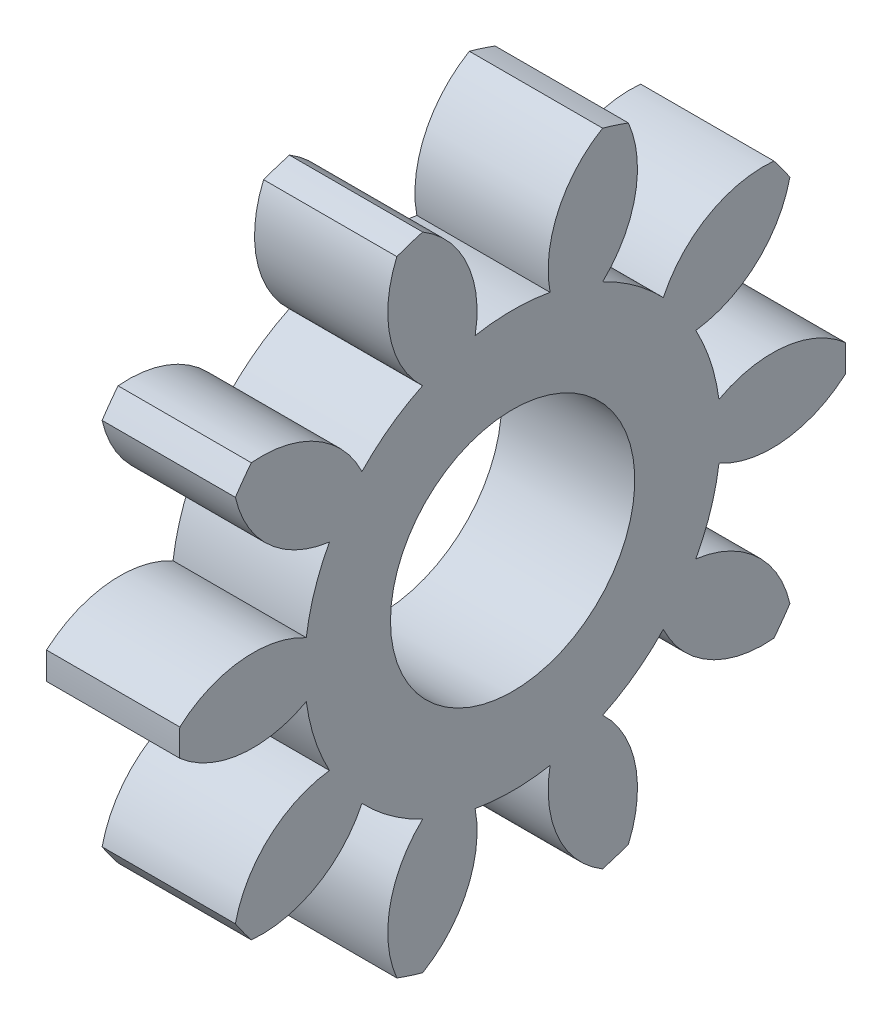
SolidWorks part; units mm, degrees
ref_plane "Plane1" through (0, 0, 0) normal (0, 0, 1) x (1, 0, 0)
ref_plane "Plane2" through (0, 0, 0) normal (0, 1, 0) x (1, 0, 0)
ref_plane "Plane3" through (0, 0, 0) normal (1, 0, 0) x (0, 0, -1)
sketch "HoldingSke" plane through (0, 0, 0) normal (0, 1, 0) x (1, 0, 0)
  line L0 (0, 0) -> (0.197, -0.0347)
  line L1 (-15, 0) -> (100, 0) construction
  line L2 (0, 0) -> (-2.1039, 2.3779)
  line L3 (0, 0) -> (-11.863, 4.5341)
  line L4 (0, 0) -> (8.5048, 1.4996)
  line L5 (0, 0) -> (-46.8476, -17.4728)
  line L6 (0, 0) -> (-9.9476, -6.7116)
  line L7 (-2.1039, 2.3779) -> (8.6586, 51.2059)
  line L8 (-76.2, 54.61) -> (-72.9, 54.61)
  line L9 (-67.7845, 28.3722) -> (-49.3413, 33.142)
  line L10 (-76.2, 71.12) -> (104.1128, 71.12)
  line L11 (0, 0) -> (-12, 0)
  line L12 (-76.2, 101.6) -> (-76.033, 101.6)
  line L13 (24.9733, 27.94) -> (52.9518, 28.4284)
  line L14 (24.9733, 27.94) -> (24.9743, 27.94)
  line L15 (24.9733, 27.94) -> (100.4006, 29.5858)
  line L16 (-63.627, -5) -> (-12.827, -5)
  circle A0 centre (0, 0) radius 11
  circle A1 centre (0, 0) radius 18.749
  circle A2 centre (0, 0) radius 37.5
  circle A3 centre (0, 0) radius 11
  dimension "MHD" = 37.498
  dimension "Hub_dia" = 75
  dimension "Bore" = 22
  dimension "MBD" = 22
  dimension "Num_teeth" = 10
  dimension "Pitch_radius" = 180.3128
  dimension "Pitch" = 0.2
  dimension "Width" = 12
  dimension "Overall_len" = 50
  dimension "Show_teeth" = 10
  dimension "Thickness" = 12
  dimension "OAL" = 50.0001
  dimension "T_dim" = 3.3
  dimension "Ap" = 14.5
  dimension "H" = 19.05
  dimension "Backlash" = 0.167
  dimension "Addendum_fac" = 1
  dimension "Dedendum_fac" = 1.25
  dimension "Clearance_fac" = 0.25
  dimension "Dedendum_add" = 0.001
  dimension "Module" = 5
sketch "BasProSke" plane through (0, 0, 0) normal (0, 1, 0) x (1, 0, 0)
  line L0 (-10, 0) -> (60, 0) construction
  line L1 (0, 0) -> (0, 30)
  line L2 (0, 0) -> (12, 0)
  line L3 (12, 0) -> (12, 30)
  line L4 (12, 30) -> (0, 30)
  dimension "Diameter" = 60
  dimension "Thickness" = 12
revolve "Base-Revolve" add sketch "BasProSke" angle 360 about L0
sketch "TooCutSke" plane through (0, 0, 0) normal (1, 0, 0) x (0, 0, -1)
  line L1 (0, 0) -> (0, 107) construction
  line L2 (0, 0) -> (-4.2026, 24.6442) construction
  line L3 (0, 0) -> (-15.2881, 47.0521) construction
  line L4 (-4.2026, 24.6442) -> (-7.6441, 23.526) construction
  arc A0 (3.374, 18.4429) -> (-3.374, 18.4429) centre (0, 0) ccw
  arc A1 (8.1303, 28.9037) -> (-8.1303, 28.9037) centre (0, 0) ccw
  circle A2 centre (0, 0) radius 25 construction
  circle A3 centre (0, 0) radius 24.2037 construction
  arc A4 (-3.374, 18.4429) -> (-8.1303, 28.9037) centre (-13.2027, 20.2856) ccw
  arc A5 (8.1303, 28.9037) -> (3.374, 18.4429) centre (13.2027, 20.2856) ccw
  dimension "Root_dia" = 37.498
  dimension "Overcut_dia" = 60.0508
  dimension "Pitch_dia" = 50
  dimension "Base_dia" = 48.4074
  dimension "Flank_rad" = 10
  dimension "Half_ang" = 18
  dimension "Half_CT" = 3.6186
extrude "ToothCut" cut sketch "TooCutSke" along normal through all
fillet "Breaks" [suppressed] radius 0.1
fillet "RootFillets" [suppressed] radius 1.251
pattern_circular "TeethCuts" count 10 every 36 about axis through (-10, 0, 0) along (1, 0, 0) of "ToothCut", "RootFillets", "Breaks"
sketch "HubNeaOneSke" plane through (0, 0, 0) normal (-1, 0, 0) x (0, 0, 1)
  circle A0 centre (0, 0) radius 18.749
  dimension "Diameter" = 37.498
extrude "HubNearOne" [suppressed] add sketch "HubNeaOneSke" along normal blind 38.0001
sketch "HubNeaBotSke" plane through (0, 0, 0) normal (-1, 0, 0) x (0, 0, 1)
  circle A0 centre (0, 0) radius 18.749
  dimension "Diameter" = 37.498
extrude "HubNearBoth" [suppressed] add sketch "HubNeaBotSke" along normal blind 19
ref_plane "FarPln" through (12, 0, 0) normal (1, 0, 0) x (0, 0, -1)
sketch "HubFarSke" plane through (12, 0, 0) normal (1, 0, 0) x (0, 0, -1)
  circle A0 centre (0, 0) radius 18.749
  dimension "Diameter" = 37.498
extrude "HubFar" [suppressed] add sketch "HubFarSke" along normal blind 19
sketch "BorSke" plane through (0, 0, 0) normal (1, 0, 0) x (0, 0, -1)
  circle A0 centre (0, 0) radius 11
  dimension "Diameter" = 22
extrude "Bore" cut sketch "BorSke" along normal mid plane 100.0001
sketch "KeySke" plane through (0, 0, 0) normal (1, 0, 0) x (0, 0, -1)
  line L0 (-4, 0) -> (-4, 14.3)
  line L1 (-4, 14.3) -> (4, 14.3)
  line L2 (4, 14.3) -> (4, 0)
  line L3 (0, 0) -> (0, 34) construction
  line L4 (-4, 0) -> (4, 0)
  dimension "Offset" = 14.3
  dimension "Width" = 8
extrude "Keyway" [suppressed] cut sketch "KeySke" along normal mid plane 100.0001
pattern_circular "Keyway2" [suppressed] count 2 every 90 about axis through (-10, 0, 0) along (1, 0, 0)
equation "' \"Module@HoldingSke\" = 6.35"
equation "' \"Num_teeth@HoldingSke\" = 12"
equation "' \"Ap@HoldingSke\" =  20"
equation "' \"Width@HoldingSke\" = 0.5 * 25.4"
equation "' \"Hub_dia@HoldingSke\"= 1 * 25.4"
equation "' \"Overall_len@HoldingSke\" = 1.0 * 25.4"
equation "' \"Bore@HoldingSke\" = 0.75 * 25.4"
equation "' \"T_dim@HoldingSke\" = 0.1 * 25.4"
equation "' \"Width@KeySke\" = 0.25 * 25.4"
equation "' \"Show_teeth@HoldingSke\" = 13"
equation "' \"Backlash@HoldingSke\" = 0.009 * 25.4"
equation "' \"Addendum_fac@HoldingSke\" = 1.0"
equation "' \"Dedendum_fac@HoldingSke\" = 1.25"
equation "' \"Dedendum_add@HoldingSke\" = 0.00005 * 25.4"
equation "' \"Clearance_fac@HoldingSke\" = 0.25"
equation "\"Pitch@HoldingSke\" = 1 / \"Module@HoldingSke\""
equation "\"Overcut_dia@TooCutSke\" = (\"Num_teeth@HoldingSke\" + 2 * \"Addendum_fac@HoldingSke\") / \"Pitch@HoldingSke\" + 0.002 * 25.4"
equation "\"Pitch_dia@TooCutSke\" = \"Num_teeth@HoldingSke\" / \"Pitch@HoldingSke\""
equation "\"Base_dia@TooCutSke\" = \"Num_teeth@HoldingSke\" / \"Pitch@HoldingSke\" * cos((\"Ap@HoldingSke\"  * 3.14159265 / 180))"
equation "\"Root_dia@TooCutSke\" = (\"Num_teeth@HoldingSke\" + 2) / \"Pitch@HoldingSke\" - 2 * (\"Addendum_fac@HoldingSke\" + \"Dedendum_fac@HoldingSke\") / \"Pitch@HoldingSke\" - \"Dedendum_add@HoldingSke\" * 2"
equation "\"Half_ang@TooCutSke\" = 180 / \"Num_teeth@HoldingSke\""
equation "\"Half_CT@TooCutSke\" = \"Num_teeth@HoldingSke\" / \"Pitch@HoldingSke\" * sin((3.14159265 / 2 / \"Num_teeth@HoldingSke\")) / 2 - 7 * \"Backlash@HoldingSke\" / 4"
equation "\"Flank_rad@TooCutSke\" = \"Num_teeth@HoldingSke\" / \"Pitch@HoldingSke\" / 5"
equation "\"Radius@RootFillets\" = \"Clearance_fac@HoldingSke\" / \"Pitch@HoldingSke\" + \"Dedendum_add@HoldingSke\""
equation "\"Break_rad@Breaks\" = 0.02 / \"Pitch@HoldingSke\""
equation "\"Thickness@HoldingSke\" = \"Width@HoldingSke\""
equation "\"OAL@HoldingSke\" = \"Thickness@HoldingSke\""
equation "\"MHD@HoldingSke\" = (\"Num_teeth@HoldingSke\" + 2) / \"Pitch@HoldingSke\" - 2 * (\"Addendum_fac@HoldingSke\" + \"Dedendum_fac@HoldingSke\")  / \"Pitch@HoldingSke\" - \"Dedendum_add@HoldingSke\" * 2"
equation "\"MBD@HoldingSke\" = (\"Num_teeth@HoldingSke\" + 2) / \"Pitch@HoldingSke\" - 2 * (\"Addendum_fac@HoldingSke\" + \"Dedendum_fac@HoldingSke\")  / \"Pitch@HoldingSke\" - \"Dedendum_add@HoldingSke\" * 2 - 0.002 * 25.4"
equation "\"MHD@HoldingSke\" = ((sgn( \"MHD@HoldingSke\" - \"Hub_dia@HoldingSke\" )-1)*( \"MHD@HoldingSke\" - \"Hub_dia@HoldingSke\" ))/-2+ \"Hub_dia@HoldingSke\""
equation "\"MBD@HoldingSke\" = ((sgn( \"MBD@HoldingSke\" - \"Bore@HoldingSke\" )-1)*( \"MBD@HoldingSke\" - \"Bore@HoldingSke\" ))/-2+ \"Bore@HoldingSke\""
equation "\"OAL@HoldingSke\" = ((sgn( \"OAL@HoldingSke\" - \"Overall_len@HoldingSke\" )+1)*( \"OAL@HoldingSke\" - \"Overall_len@HoldingSke\" ))/2 + \"Overall_len@HoldingSke\" + 0.000002 * 25.4"
equation "\"Num_teeth@TeethCuts\" = int( \"Show_teeth@HoldingSke\" ) + 1"
equation "\"Num_teeth@TeethCuts\" = ((sgn( \"Num_teeth@TeethCuts\" - \"Num_teeth@HoldingSke\" )-1)*( \"Num_teeth@TeethCuts\" - \"Num_teeth@HoldingSke\" ))/-2+ \"Num_teeth@HoldingSke\""
equation "\"Num_teeth@TeethCuts\" = ((sgn( \"Num_teeth@TeethCuts\" - 2.0)+1)*( \"Num_teeth@TeethCuts\" - 2.0))/2 +2.0"
equation "\"Angle@TeethCuts\" = 360.0 / \"Num_teeth@HoldingSke\""
equation "\"Diameter@BasProSke\" = (\"Num_teeth@HoldingSke\" + 2 * \"Addendum_fac@HoldingSke\") / \"Pitch@HoldingSke\""
equation "\"Thickness@BasProSke\"  = \"Thickness@HoldingSke\""
equation "' \"Fillet_rad@BasProSke\" =  \"Thickness@HoldingSke\" * 0.05"
equation "\"MHD@HoldingSke\" = ((sgn( \"MHD@HoldingSke\" - \"Root_dia@TooCutSke\" )-1)*( \"MHD@HoldingSke\" - \"Root_dia@TooCutSke\" ))/-2+ \"Root_dia@TooCutSke\""
equation "\"Diameter@HubNeaOneSke\" = \"MHD@HoldingSke\""
equation "\"Length@HubNearOne\" = \"OAL@HoldingSke\" - \"Thickness@BasProSke\""
equation "\"Diameter@HubNeaBotSke\" = \"MHD@HoldingSke\""
equation "\"Length@HubNearBoth\" = ( \"OAL@HoldingSke\" - \"Thickness@BasProSke\" ) / 2.0"
equation "\"Thickness@FarPln\" = \"Thickness@BasProSke\""
equation "\"Diameter@HubFarSke\" = \"MHD@HoldingSke\""
equation "\"Length@HubFar\" = ( \"OAL@HoldingSke\" - \"Thickness@BasProSke\" ) / 2.0"
equation "\"Diameter@BorSke\" = \"MBD@HoldingSke\""
equation "\"D1@Bore\" = \"OAL@HoldingSke\" * 2.0"
equation "\"D1@Keyway\" = \"OAL@HoldingSke\" * 2.0"
equation "\"Offset@KeySke\" = \"T_dim@HoldingSke\" + \"MBD@HoldingSke\" / 2.0"
